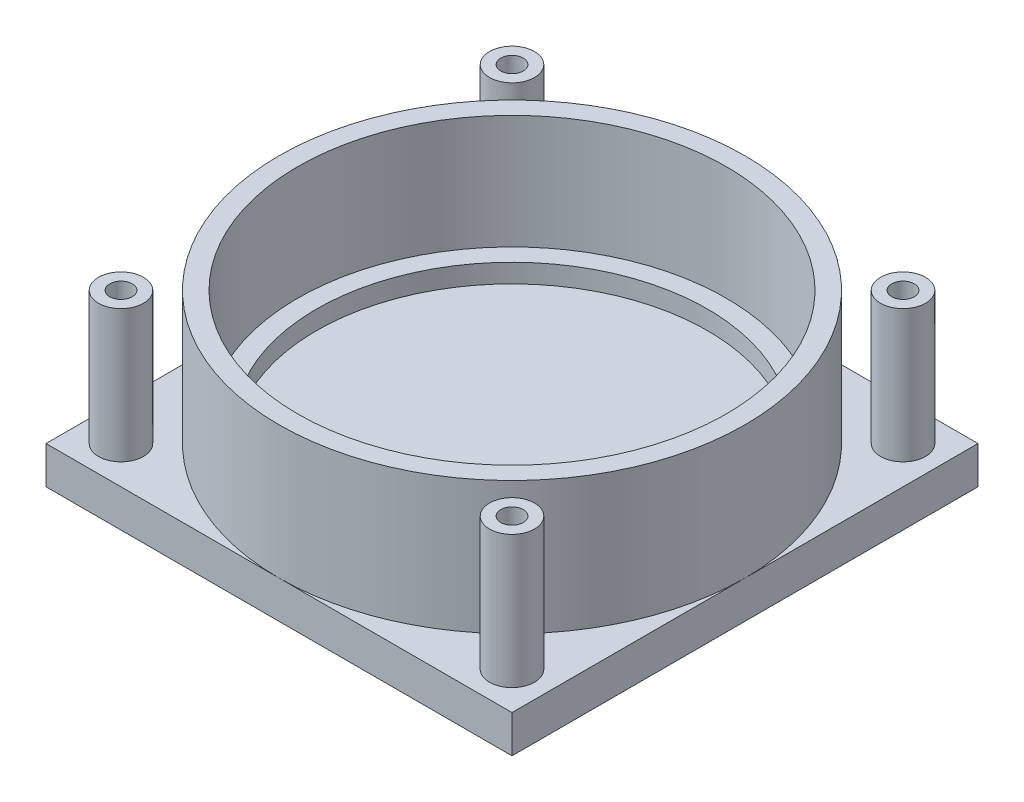
SolidWorks part; units mm, degrees
ref_plane "Front Plane" through (0, 0, 0) normal (0, 0, 1) x (1, 0, 0)
ref_plane "Top Plane" through (0, 0, 0) normal (0, 1, 0) x (1, 0, 0)
ref_plane "Right Plane" through (0, 0, 0) normal (1, 0, 0) x (0, 0, -1)
sketch "Sketch1" plane through (0, 0, 0) normal (0, 1, 0) x (1, 0, 0)
  line L1 (-31.075, 31.075) -> (31.075, 31.075)
  line L2 (-31.075, 31.075) -> (-31.075, -31.075)
  line L3 (-31.075, -31.075) -> (31.075, -31.075)
  line L4 (31.075, 31.075) -> (31.075, -31.075)
  line L5 (-31.075, 31.075) -> (31.075, -31.075) construction
  line L6 (-31.075, -31.075) -> (31.075, 31.075) construction
  point P0 (0, 0)
  dimension "D1" = 62.15
  dimension "D2" = 62.15
extrude "Boss-Extrude1" add sketch "Sketch1" along normal blind 5
sketch "Sketch3" plane through (0, 5, 0) normal (0, 1, 0) x (1, 0, 0)
  line L0 (31.075, -31.075) -> (31.075, 31.075) construction
  circle A0 centre (0, 0) radius 31.075
extrude "Boss-Extrude2" add sketch "Sketch3" along normal blind 17.7
sketch "Sketch4" plane through (0, 22.7, 0) normal (0, 1, 0) x (1, 0, 0)
  circle A0 centre (0, 0) radius 28.575
  dimension "D1" = 57.15
extrude "Cut-Extrude2" cut sketch "Sketch4" against normal blind 17.7
sketch "Sketch5" plane through (0, 5, 0) normal (0, 1, 0) x (1, 0, 0)
  circle A0 centre (0, 0) radius 28.575
  circle A1 centre (0, 0) radius 26.075
  dimension "D1" = 52.15
  dimension "D2" = 57.15
extrude "Boss-Extrude3" add sketch "Sketch5" along normal blind 2.5
sketch "Sketch8" plane through (0, 5, 0) normal (0, 1, 0) x (1, 0, 0)
  line L0 (-31.075, 31.075) -> (-31.075, 0) construction
  line L1 (0, 31.075) -> (-31.075, 31.075) construction
  line L2 (0, 31.075) -> (0, -31.075) construction
  line L3 (31.075, 0) -> (-31.075, 0) construction
  circle A0 centre (-26.075, 26.075) radius 1.5
  circle A1 centre (0, 0) radius 31.075 construction
  circle A2 centre (-26.075, -26.075) radius 1.5
  circle A3 centre (26.075, -26.075) radius 1.5
  circle A4 centre (26.075, 26.075) radius 1.5
  dimension "D1" = 3
  dimension "D2" = 5
  dimension "D3" = 5
extrude "Cut-Extrude4" cut sketch "Sketch8" against normal up to next
sketch "Sketch9" plane through (0, 5, 0) normal (0, 1, 0) x (1, 0, 0)
  line L0 (0, 31.075) -> (0, -31.075) construction
  line L1 (31.075, 0) -> (-31.075, 0) construction
  circle A0 centre (-26.075, 26.075) radius 3
  circle A1 centre (-26.075, 26.075) radius 1.5
  circle A2 centre (-26.075, -26.075) radius 3
  circle A3 centre (-26.075, -26.075) radius 1.5
  circle A4 centre (26.075, -26.075) radius 1.5
  circle A5 centre (26.075, -26.075) radius 3
  circle A6 centre (26.075, 26.075) radius 3
  circle A7 centre (26.075, 26.075) radius 1.5
  dimension "D1" = 3
  dimension "D2" = 6
extrude "Boss-Extrude5" add sketch "Sketch9" along normal blind 17.7
equation "\"D2@Sketch1\"=\"D1@Sketch1\""
equation "\"D1@Sketch5\"=\"D2@Sketch5\"-5"
equation "\"D1@Boss-Extrude3\"=17.7-12.7-2.5"
